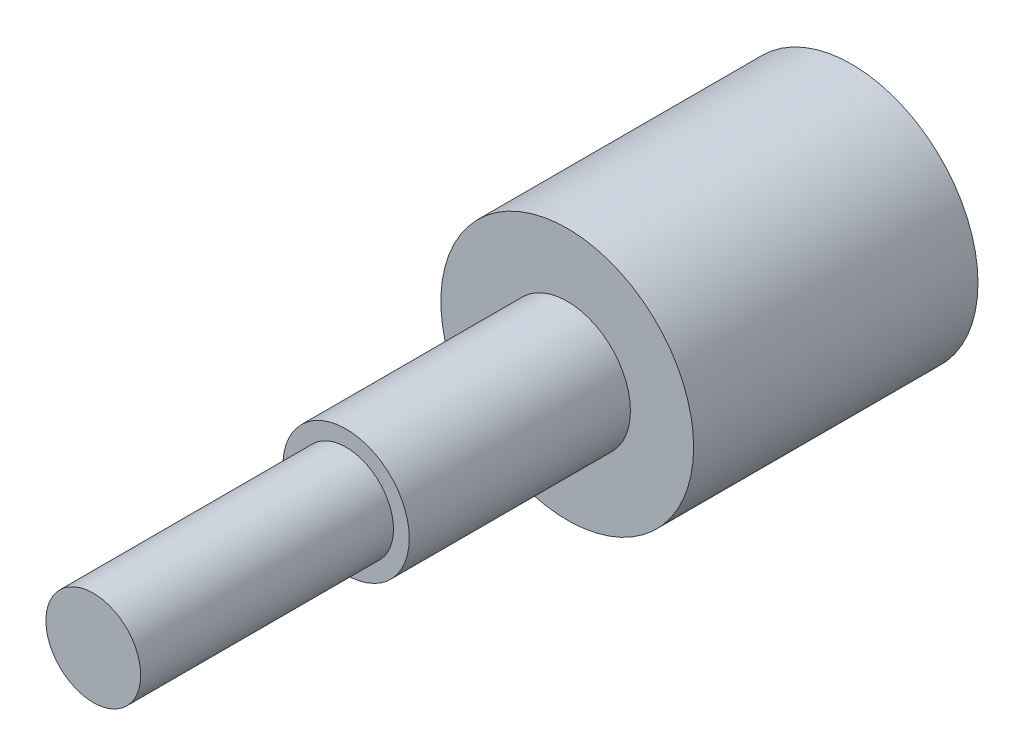
SolidWorks part; units mm, degrees
material "AISI 304"
ref_plane "Front" through (0, 0, 0) normal (0, 0, 1) x (1, 0, 0)
ref_plane "Top" through (0, 0, 0) normal (0, 1, 0) x (1, 0, 0)
ref_plane "Right" through (0, 0, 0) normal (1, 0, 0) x (0, 0, -1)
sketch "Sketch1" plane through (0, 0, 0) normal (0, 0, 1) x (1, 0, 0)
  circle A0 centre (0, 0) radius 4
  dimension "D1" = 8
extrude "Boss-Extrude1" add sketch "Sketch1" along normal blind 9
sketch "Sketch2" plane through (0, 0, 9) normal (0, 0, 1) x (1, 0, 0)
  circle A0 centre (0, 0) radius 2
  dimension "D1" = 4
extrude "Boss-Extrude2" add sketch "Sketch2" along normal blind 7
sketch "Sketch3" plane through (0, 0, 16) normal (0, 0, 1) x (1, 0, 0)
  circle A0 centre (0, 0) radius 1.5
  dimension "D1" = 3
extrude "Boss-Extrude3" add sketch "Sketch3" along normal blind 8
